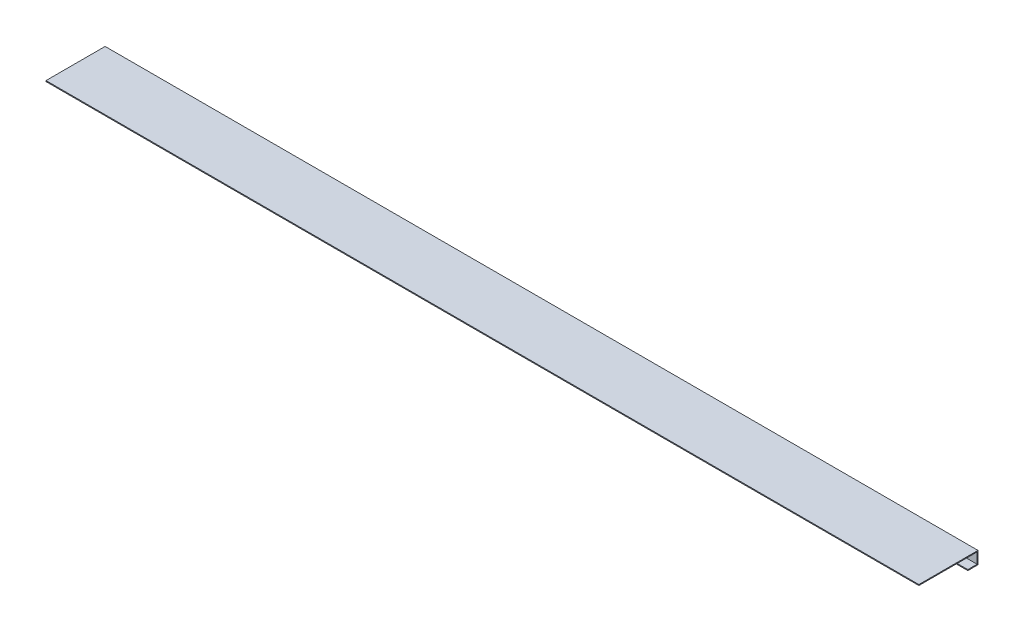
SolidWorks part; units mm, degrees
ref_plane "Front Plane" through (0, 0, 0) normal (0, 0, 1) x (1, 0, 0)
ref_plane "Top Plane" through (0, 0, 0) normal (0, 1, 0) x (1, 0, 0)
ref_plane "Right Plane" through (0, 0, 0) normal (1, 0, 0) x (0, 0, -1)
sketch "Sketch1" plane through (0, 0, 0) normal (1, 0, 0) x (0, 0, -1)
  line L0 (0, 0) -> (128, 0)
  line L1 (128, 0) -> (128, -27)
  line L2 (128, -27) -> (106, -27)
  line L3 (0, -2) -> (126, -2)
  line L4 (126, -2) -> (126, -25)
  line L5 (126, -25) -> (106, -25)
  line L6 (0, 0) -> (0, -2)
  line L7 (106, -27) -> (106, -25)
  dimension "D1" = 2
  dimension "D2" = 128
  dimension "D3" = 27
  dimension "D4" = 22
extrude "Boss-Extrude1" add sketch "Sketch1" along normal blind 1890
equation "\"door_base_long7_BR_Single_height\"=1890.0"
equation "\"D1@Boss-Extrude1\"=\"door_base_long7_BR_Single_height\""
equation "\"CarBeamWidth\"=700.0"
equation "\"WheelWidth\"=650.0"
equation "\"Wheel_FrontBoxDistance\"=1390.0"
equation "\"boxLength\"=5100.0"
equation "\"boxWidth\"=1930.0"
equation "\"MetalSheet_3mm_length\"=5030.0"
equation "\"MetalSheet_3mm_width\"=1923.0"
equation "\"MetalSheet_3mm_FloorCut_L_length\"=1764.0"
equation "\"MetalSheet_3mm_FloorCut_L_disdance\"=1665.0"
equation "\"MetalSheet_3mm_FloorCut_R_length\"=1764.0"
equation "\"MetalSheet_3mm_FloorCut_R_disdance\"=1665.0"
equation "\"indoorHeight\"=1940.0"
equation "\"indoorHeight_para\"=25.0"
equation "\"rearLightHeight_para\"=265.0"
equation "\"haveDoor_R\"=1"
equation "\"side_door_bottom_R_3mm_length\"=1934.0"
equation "\"side_door_bottom_R_3mm_toFrontDistance\"=1583.0"
equation "\"1Bar_Side_RF_3mm_length\"=1493.0"
equation "\"1Bar_Side_RB_3mm_length\"=1493.0"
equation "\"DoorSeparator_RF_3mm_withHinge_toFrontDistance\"=1673.0"
equation "\"DoorSeparator_RF_3mm_withHinge_exist\"=1"
equation "\"DoorSeparator_RB_3mm_withHinge_toFrontDistance\"=3427.0"
equation "\"DoorSeparator_RB_3mm_withHinge_exist\"=1"
equation "\"Door_R1_L_open_Single_toFrontDistance\"=2547.5"
equation "\"Door_R1_L_open_Single_exist\"=1"
equation "\"door_base_long7_R1_L_open_Single_height\"=1890.0"
equation "\"door_base_short7_R1_L_open_Single_height\"=1890.0"
equation "\"door_base_short7_R1_L_open_Single_width\"=864"
equation "\"Door_R1_R_open_Single_toFrontDistance\"=3422.0"
equation "\"Door_R1_R_open_Single_exist\"=1"
equation "\"door_base_long7_R1_R_open_Single_height\"=1890.0"
equation "\"door_base_short7_R1_R_open_Single_height\"=1890.0"
equation "\"door_base_short7_R1_R_open_Single_width\"=864"
equation "\"x\"=66.0"
equation "\"door_base_double_BL_height\"=1890.0"
equation "\"door_base_short7_BL_Single_height\"=1890.0"
equation "\"door_base_short7_BL_Single_width\"=864"
equation "\"door_base_short7_BR_Single_height\"=1890.0"
equation "\"door_base_short7_BR_Single_width\"=864"
equation "\"da\"=62.0"
equation "\"SquareTube_length\"=1923.0"
equation "\"channelSteel_length\"=5030.0"
equation "\"SquareTube_inFront_AvgDistance\"=285.0"
equation "\"SquareTube_inFront_TotalCount\"=5"
equation "\"SquareTube_inFront1_cutDepth50_R\"=0.5"
equation "\"SquareTube_inFront1_cutDepth50_L\"=0.5"
equation "\"SquareTube_inFront2_cutDepth50_R\"=0.5"
equation "\"SquareTube_inFront2_cutDepth50_L\"=0.5"
equation "\"SquareTube_inFront3_cutDepth50_R\"=0.5"
equation "\"SquareTube_inFront3_cutDepth50_L\"=0.5"
equation "\"SquareTube_inFront4_cutDepth50_R\"=0.5"
equation "\"SquareTube_inFront4_cutDepth50_L\"=0.5"
equation "\"SquareTube_inFront5_cutDepth50_R\"=50"
equation "\"SquareTube_inFront5_cutDepth50_L\"=50"
equation "\"SquareTube_inFront6_cutDepth50_R\"=50"
equation "\"SquareTube_inFront6_cutDepth50_L\"=50"
equation "\"SquareTube_inFront7_cutDepth50_R\"=50"
equation "\"SquareTube_inFront7_cutDepth50_L\"=50"
equation "\"SquareTube_inFront8_cutDepth50_R\"=50"
equation "\"SquareTube_inFront8_cutDepth50_L\"=50"
equation "\"SquareTube_inFront9_cutDepth50_R\"=50"
equation "\"SquareTube_inFront9_cutDepth50_L\"=50"
equation "\"SquareTube_inFront10_cutDepth50_R\"=50"
equation "\"SquareTube_inFront10_cutDepth50_L\"=50"
equation "\"SquareTube_inFront11_cutDepth50_R\"=50"
equation "\"SquareTube_inFront11_cutDepth50_L\"=50"
equation "\"SquareTube_inFront12_cutDepth50_R\"=50"
equation "\"SquareTube_inFront12_cutDepth50_L\"=50"
equation "\"SquareTube_inFront13_cutDepth50_R\"=50"
equation "\"SquareTube_inFront13_cutDepth50_L\"=50"
equation "\"SquareTube_inFront14_cutDepth50_R\"=50"
equation "\"SquareTube_inFront14_cutDepth50_L\"=50"
equation "\"SquareTube_inBack_AvgDistance\"=333.125"
equation "\"SquareTube_inBack_TotalCount\"=9"
equation "\"SquareTube_inBack1_cutDepth50_R\"=50"
equation "\"SquareTube_inBack1_cutDepth50_L\"=50"
equation "\"SquareTube_inBack2_cutDepth50_R\"=50"
equation "\"SquareTube_inBack2_cutDepth50_L\"=50"
equation "\"SquareTube_inBack3_cutDepth50_R\"=50"
equation "\"SquareTube_inBack3_cutDepth50_L\"=50"
equation "\"SquareTube_inBack4_cutDepth50_R\"=50"
equation "\"SquareTube_inBack4_cutDepth50_L\"=50"
equation "\"SquareTube_inBack5_cutDepth50_R\"=50"
equation "\"SquareTube_inBack5_cutDepth50_L\"=50"
equation "\"SquareTube_inBack6_cutDepth50_R\"=0.5"
equation "\"SquareTube_inBack6_cutDepth50_L\"=0.5"
equation "\"SquareTube_inBack7_cutDepth50_R\"=0.5"
equation "\"SquareTube_inBack7_cutDepth50_L\"=0.5"
equation "\"SquareTube_inBack8_cutDepth50_R\"=0.5"
equation "\"SquareTube_inBack8_cutDepth50_L\"=0.5"
